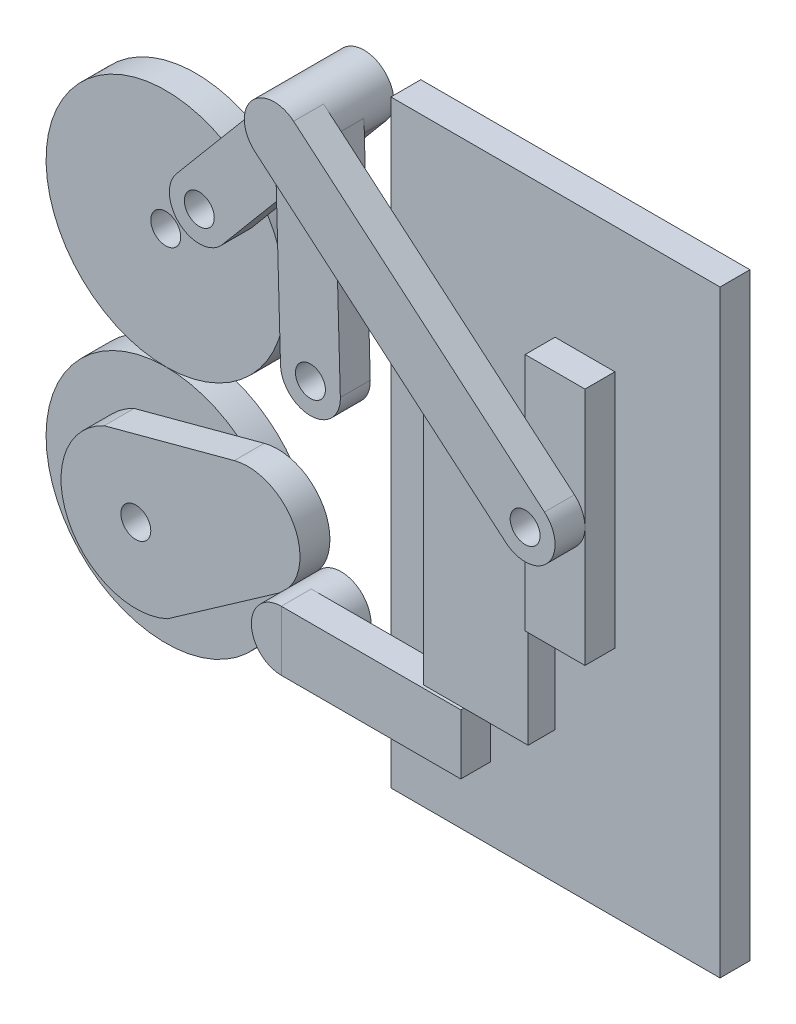
SolidWorks part; units mm, degrees
ref_plane "前视基准面" through (0, 0, 0) normal (0, 0, 1) x (1, 0, 0)
ref_plane "上视基准面" through (0, 0, 0) normal (0, 1, 0) x (1, 0, 0)
ref_plane "右视基准面" through (0, 0, 0) normal (1, 0, 0) x (0, 0, -1)
sketch "草图1" plane through (0, 0, 0) normal (0, 0, 1) x (1, 0, 0)
  line L0 (0, 88.6781) -> (0, -130.0364) construction
  circle A0 centre (0, 0) radius 40
  circle A1 centre (0, -80) radius 40
  dimension "D1" = 80
  dimension "D2" = 80
extrude "凸台-拉伸1" add sketch "草图1" along normal blind 10 contours A0
sketch "草图2" plane through (0, 0, 0) normal (0, 0, 1) x (1, 0, 0)
  line L0 (0, 51.5776) -> (0, -115.0476) construction
  circle A0 centre (0, -80) radius 40
  circle A1 centre (0, 0) radius 40 construction
  dimension "D1" = 80
extrude "凸台-拉伸2" add sketch "草图2" along normal blind 10 separate body
sketch "草图3" plane through (0, 0, 10) normal (0, 0, 1) x (1, 0, 0)
  line L0 (-49.8893, -80) -> (73.6733, -80) construction
  line L1 (0, -129.5009) -> (0, -43.5196) construction
  line L2 (-10.5655, -57.3423) -> (32.9012, -45.6954)
  line L3 (-10.5655, -57.3423) -> (10.5655, -102.6577) construction
  line L4 (-22.6577, -90.5655) -> (29.4261, -66.2784) construction
  line L5 (10.5655, -102.6577) -> (47.4273, -76.8468)
  arc A0 (10.5655, -102.6577) -> (-10.5655, -57.3423) centre (0, -80) cw
  arc A2 (47.4273, -76.8468) -> (32.9012, -45.6954) centre (37.4178, -62.5518) ccw
  dimension "D1" = 25
  dimension "D4" = 17.451
  dimension "D5" = 25
  dimension "D6" = 80
  dimension "D2" = 80
  dimension "D3" = 45
extrude "凸台-拉伸3" add sketch "草图3" along normal blind 10
sketch "草图4" plane through (0, 0, 0) normal (0, 0, 1) x (1, 0, 0)
  line L0 (0, -80) -> (116.6953, -80) construction
  circle A0 centre (58.6102, -80) radius 10
  arc A1 (47.4273, -76.8468) -> (32.9012, -45.6954) centre (37.4178, -62.5518) ccw construction
  dimension "D1" = 20
extrude "凸台-拉伸4" add sketch "草图4" along normal blind 20 from offset 10
sketch "草图5" plane through (0, 0, 30) normal (0, 0, 1) x (1, 0, 0)
  line L0 (58.6102, -70) -> (58.6102, -90)
  line L1 (58.6102, -90) -> (118.6102, -90)
  line L2 (118.6102, -90) -> (118.6102, -70)
  line L3 (118.6102, -70) -> (58.6102, -70)
  circle A0 centre (58.6102, -80) radius 10 construction
  dimension "D1" = 60
  dimension "D2" = 20
extrude "凸台-拉伸5" add sketch "草图5" against normal blind 10 separate body
sketch "草图6" plane through (0, 0, 10) normal (0, 0, 1) x (1, 0, 0)
  line L0 (0, 0) -> (40, 0) construction
  line L1 (0, 0) -> (21.2132, 21.2132) construction
  circle A0 centre (0, 0) radius 40 construction
  circle A1 centre (21.2132, 21.2132) radius 5
  dimension "D3" = 10
  dimension "D1" = 45
  dimension "D2" = 30
extrude "切除-拉伸1" cut sketch "草图6" against normal blind 10
sketch "草图7" plane through (0, 0, 10) normal (0, 0, 1) x (1, 0, 0)
  line L0 (13.5582, 27.6476) -> (58.5986, 81.2326)
  line L1 (28.8682, 14.7789) -> (73.9087, 68.3639)
  arc A0 (13.5582, 27.6476) -> (28.8682, 14.7789) centre (21.2132, 21.2132) ccw
  arc A2 (73.9087, 68.3639) -> (58.5986, 81.2326) centre (66.2536, 74.7983) ccw
  dimension "D1" = 10
  dimension "D2" = 70
  dimension "D3" = 70
extrude "凸台-拉伸6" add sketch "草图7" along normal blind 10
sketch "草图8" plane through (0, 0, 20) normal (0, 0, 1) x (1, 0, 0)
  circle A0 centre (66.2536, 74.7983) radius 5
  dimension "D1" = 10
extrude "切除-拉伸2" cut sketch "草图8" against normal blind 10
sketch "草图9" plane through (0, 0, 20) normal (0, 0, 1) x (1, 0, 0)
  line L0 (0, 0) -> (105.9248, 0) construction
  line L1 (58.3539, -0.2802) -> (56.2576, 74.5181)
  line L4 (76.2497, 75.0784) -> (78.3461, 0.2802)
  arc A1 (78.3461, 0.2802) -> (58.3539, -0.2802) centre (68.35, 0) cw
  arc A4 (76.2497, 75.0784) -> (56.2576, 74.5181) centre (66.2536, 74.7983) ccw
  arc A5 (73.9087, 68.3639) -> (58.5986, 81.2326) centre (66.2536, 74.7983) ccw construction
  dimension "D1" = 10
  dimension "D2" = 68.35
extrude "凸台-拉伸7" add sketch "草图9" along normal blind 10
sketch "草图10" plane through (0, 0, 30) normal (0, 0, 1) x (1, 0, 0)
  line L0 (59.7813, 67.1754) -> (143.6329, -4.0208)
  line L1 (72.726, 82.4211) -> (156.5777, 11.225)
  arc A1 (156.5777, 11.225) -> (143.6329, -4.0208) centre (150.1053, 3.6021) cw
  arc A2 (59.7813, 67.1754) -> (72.726, 82.4211) centre (66.2536, 74.7983) cw
  arc A3 (76.2497, 75.0784) -> (56.2576, 74.5181) centre (66.2536, 74.7983) ccw construction
  dimension "D1" = 10
  dimension "D2" = 110
extrude "凸台-拉伸9" add sketch "草图10" along normal blind 10
sketch "草图12" plane through (0, 0, 30) normal (0, 0, 1) x (1, 0, 0)
  circle A0 centre (68.35, 0) radius 5
  dimension "D1" = 10
extrude "切除-拉伸3" cut sketch "草图12" against normal blind 10
sketch "草图13" plane through (0, 0, 20) normal (0, 0, 1) x (1, 0, 0)
  circle A0 centre (21.2132, 21.2132) radius 5
  dimension "D1" = 10
extrude "切除-拉伸4" cut sketch "草图13" against normal blind 10
sketch "草图14" plane through (0, 0, 40) normal (0, 0, 1) x (1, 0, 0)
  circle A0 centre (150.1053, 3.6021) radius 5
  dimension "D1" = 10
extrude "切除-拉伸5" cut sketch "草图14" against normal blind 10
sketch "草图15" plane through (0, 0, 30) normal (0, 0, -1) x (-1, 0, 0)
  line L1 (-160.1053, -36.3979) -> (-140.1053, -36.3979)
  line L2 (-160.1053, -36.3979) -> (-160.1053, 43.6021)
  line L3 (-160.1053, 43.6021) -> (-140.1053, 43.6021)
  line L4 (-140.1053, -36.3979) -> (-140.1053, 43.6021)
  line L5 (-150.1053, 43.6021) -> (-150.1053, -36.3979) construction
  line L6 (-160.1053, 3.6021) -> (-140.1053, 3.6021) construction
  point P0 (-150.1053, 3.6021)
  dimension "D1" = 80
  dimension "D2" = 20
extrude "凸台-拉伸10" add sketch "草图15" along normal blind 10 separate body
sketch "草图16" plane through (0, 0, 20) normal (0, 0, -1) x (-1, 0, 0)
  line L1 (-195.239, 85.7115) -> (-85.239, 85.7115)
  line L2 (-195.239, 85.7115) -> (-195.239, -114.2885)
  line L3 (-195.239, -114.2885) -> (-85.239, -114.2885)
  line L4 (-85.239, 85.7115) -> (-85.239, -114.2885)
  dimension "D1" = 110
  dimension "D2" = 200
extrude "凸台-拉伸11" add sketch "草图16" along normal blind 10
sketch "草图17" plane through (0, 0, 20) normal (0, 0, 1) x (1, 0, 0)
  line L1 (140.1053, -70) -> (105.1053, -70)
  line L2 (140.1053, -70) -> (140.1053, 15)
  line L3 (140.1053, 15) -> (105.1053, 15)
  line L4 (105.1053, -70) -> (105.1053, 15)
  dimension "D1" = 35
  dimension "D2" = 85
extrude "凸台-拉伸12" add sketch "草图17" along normal blind 9
sketch "草图18" plane through (0, 0, 10) normal (0, 0, 1) x (1, 0, 0)
  circle A0 centre (0, 0) radius 5
  dimension "D1" = 10
extrude "切除-拉伸6" cut sketch "草图18" against normal blind 10
sketch "草图19" plane through (0, 0, 20) normal (0, 0, 1) x (1, 0, 0)
  circle A0 centre (0, -80) radius 5
  dimension "D1" = 10
extrude "切除-拉伸7" cut sketch "草图19" against normal blind 20
